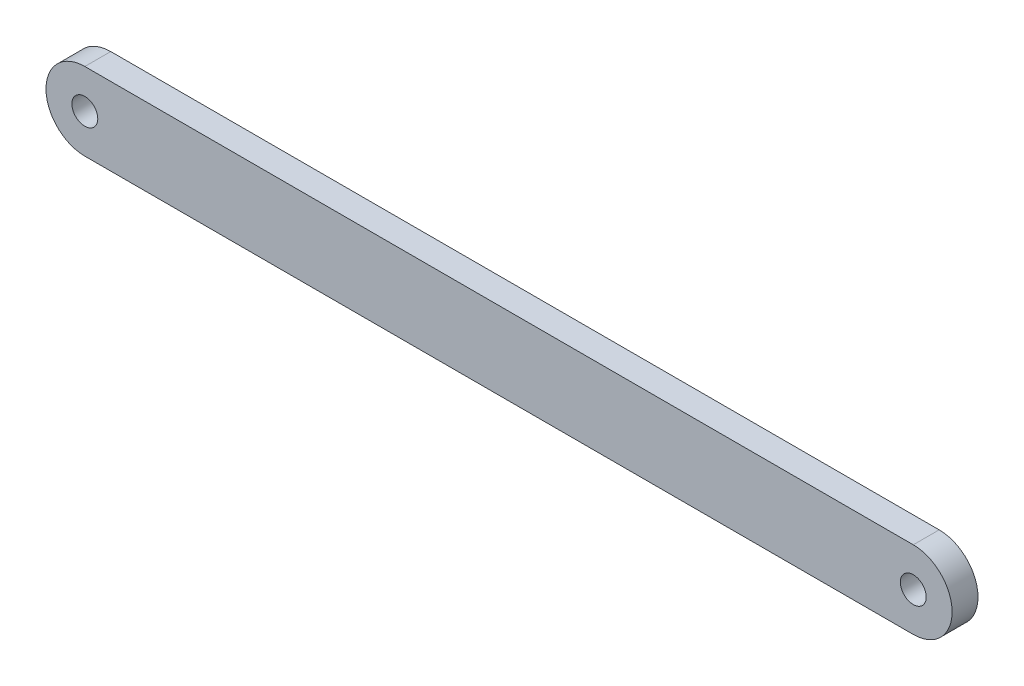
SolidWorks part; units mm, degrees
material "Hexcel AS4C (3000 Filaments)"
ref_plane "Front Plane" through (0, 0, 0) normal (0, 0, 1) x (1, 0, 0)
ref_plane "Top Plane" through (0, 0, 0) normal (0, 1, 0) x (1, 0, 0)
ref_plane "Right Plane" through (0, 0, 0) normal (1, 0, 0) x (0, 0, -1)
sketch "Sketch1" plane through (0, 0, 0) normal (0, 0, 1) x (1, 0, 0)
  line L0 (0, 4.7625) -> (101.6, 4.7625)
  line L1 (0, -4.7625) -> (101.6, -4.7625)
  circle A0 centre (0, 0) radius 1.5875
  circle A1 centre (101.6, 0) radius 1.5875
  circle A2 centre (0, 0) radius 4.7625
  circle A3 centre (101.6, 0) radius 4.7625
  dimension "D1" = 101.6
  dimension "D2" = 3.175
  dimension "D3" = 9.525
extrude "Boss-Extrude1" add sketch "Sketch1" along normal blind 3.175 contours A3 L0 A2 L1 | A2 A0 | A3 A1
